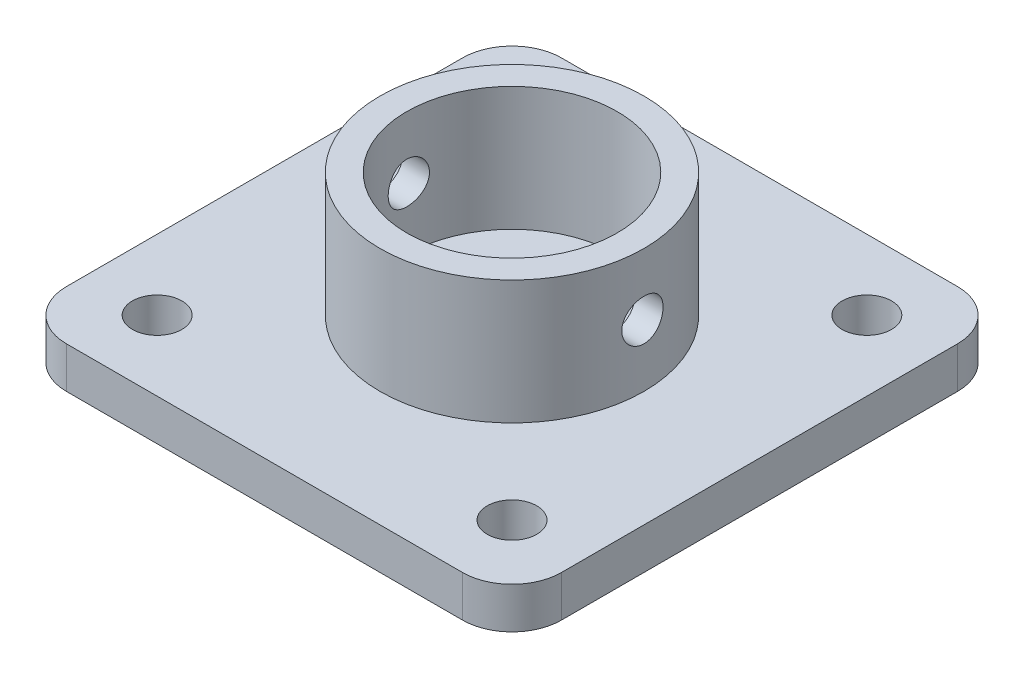
SolidWorks part; units mm, degrees
material "3.3547 (EN-AW 5083)"
ref_plane "Front Plane" through (0, 0, 0) normal (0, 0, 1) x (1, 0, 0)
ref_plane "Top Plane" through (0, 0, 0) normal (0, 1, 0) x (1, 0, 0)
ref_plane "Right Plane" through (0, 0, 0) normal (1, 0, 0) x (0, 0, -1)
sketch "Sketch1" plane through (0, 0, 0) normal (0, 1, 0) x (1, 0, 0)
  line L0 (0, -44.7868) -> (0, 44.7868) construction
  line L1 (-30, -30) -> (30, -30)
  line L2 (-30, -30) -> (-30, 30)
  line L3 (-30, 30) -> (30, 30)
  line L4 (30, -30) -> (30, 30)
  line L5 (-44.2539, 0) -> (44.2539, 0) construction
  circle A0 centre (21.5, 21.5) radius 3
  circle A1 centre (-21.5, 21.5) radius 3
  circle A2 centre (-21.5, -21.5) radius 3
  circle A3 centre (21.5, -21.5) radius 3
  point P0 (0, 0)
  point P5 (0, 30)
  point P9 (30, 0)
  dimension "D3" = 6
  dimension "D4" = 43
  dimension "D1" = 60
  dimension "D2" = 60
  dimension "D5" = 43
  dimension "D6" = 21.5
  dimension "D7" = 21.5
extrude "Boss-Extrude1" add sketch "Sketch1" along normal blind 5
fillet "Fillet1" radius 6 4 edges at (-30, 2.5, 30) (-30, 2.5, -30) (30, 2.5, -30) (30, 2.5, 30)
sketch "Sketch2" plane through (0, 5, 0) normal (0, 1, 0) x (1, 0, 0)
  circle A0 centre (0, 0) radius 12.75
  circle A1 centre (0, 0) radius 16
  dimension "D1" = 25.5
  dimension "D2" = 32
extrude "Boss-Extrude2" add sketch "Sketch2" along normal blind 15
sketch "Sketch3" plane through (0, 0, 0) normal (1, 0, 0) x (0, 0, -1)
  line L0 (0, 44.2539) -> (0, -44.2539) construction
  line L1 (-24, 5) -> (24, 5) construction
  circle A0 centre (0, 12.5) radius 2.5
  dimension "D1" = 5
  dimension "D2" = 7.5
extrude "Cut-Extrude1" cut sketch "Sketch3" against normal through all both and the other way through all
